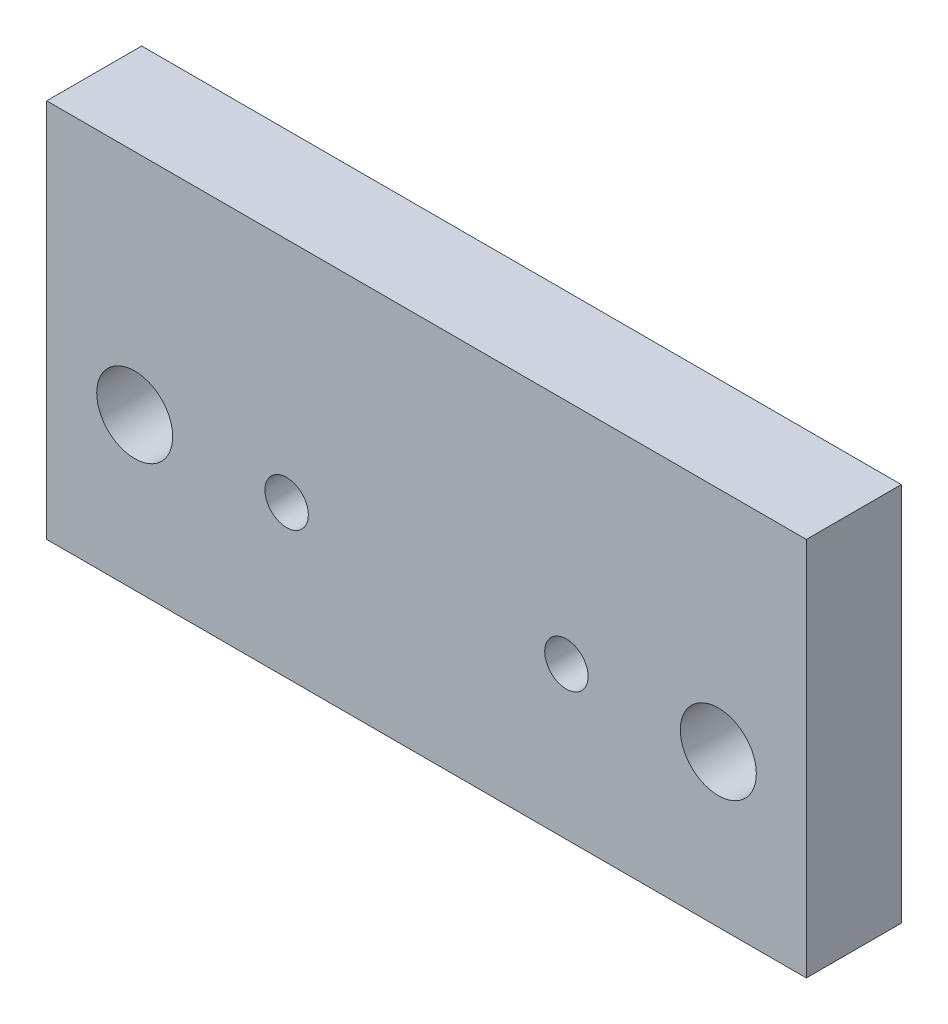
SolidWorks part; units mm, degrees
ref_plane "Front Plane" through (0, 0, 0) normal (0, 0, 1) x (1, 0, 0)
ref_plane "Top Plane" through (0, 0, 0) normal (0, 1, 0) x (1, 0, 0)
ref_plane "Right Plane" through (0, 0, 0) normal (1, 0, 0) x (0, 0, -1)
sketch "Sketch1" plane through (0, 0, 0) normal (0, 0, 1) x (1, 0, 0)
  line L1 (-20, 10) -> (20, 10)
  line L2 (-20, 10) -> (-20, -10)
  line L3 (-20, -10) -> (20, -10)
  line L4 (20, 10) -> (20, -10)
  dimension "D1" = 40
  dimension "D2" = 20
  dimension "D3" = 20
  dimension "D4" = 10
extrude "Boss-Extrude1" add sketch "Sketch1" along normal blind 5
sketch "Sketch2" plane through (0, 0, 0) normal (0, 0, -1) x (-1, 0, 0)
  line L0 (20, -10) -> (-20, -10) construction
  line L1 (20, 10) -> (20, -10) construction
  line L2 (-20, -10) -> (-20, 10) construction
  circle A1 centre (7.366, -2) radius 1.143
  circle A3 centre (-7.366, -2) radius 1.143
  circle A4 centre (-15.366, -2) radius 2
  circle A5 centre (15.366, -2) radius 2
  point P10 (0, 0)
  point P11 (0, 0)
  point P12 (0, 0)
  point P17 (0, 0)
  point P18 (0, 0)
  dimension "D1" = 4
  dimension "D2" = 4
  dimension "D7" = 2.286
  dimension "D8" = 2.286
  dimension "D3" = 8
  dimension "D4" = 8
  dimension "D5" = 8
  dimension "D6" = 4.634
  dimension "D9" = 4.634
  dimension "D10" = 8
extrude "Cut-Extrude1" cut sketch "Sketch2" against normal blind 10
